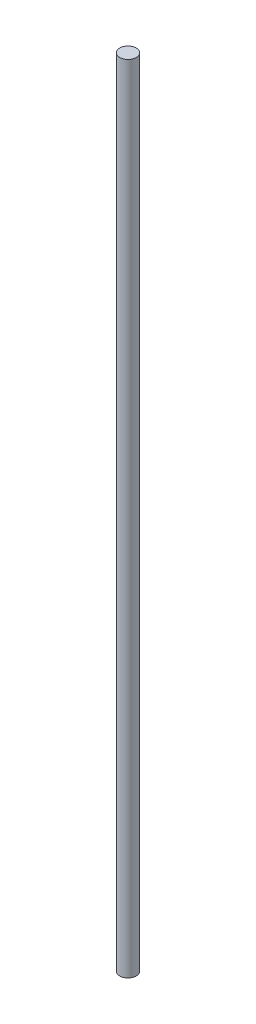
SolidWorks part; units mm, degrees
ref_plane "Front Plane" through (0, 0, 0) normal (0, 0, 1) x (1, 0, 0)
ref_plane "Top Plane" through (0, 0, 0) normal (0, 1, 0) x (1, 0, 0)
ref_plane "Right Plane" through (0, 0, 0) normal (1, 0, 0) x (0, 0, -1)
sketch "Sketch1" plane through (0, 0, 0) normal (0, 1, 0) x (1, 0, 0)
  circle A0 centre (0, 0) radius 4
  dimension "D1" = 8
extrude "Boss-Extrude1" add sketch "Sketch1" along normal blind 385.75
equation "\"d\"= 8"
equation "\"l\" = 385.75"
equation "\"D1@Boss-Extrude1\"=\"l\""
equation "\"D1@Sketch1\"=\"d\""
